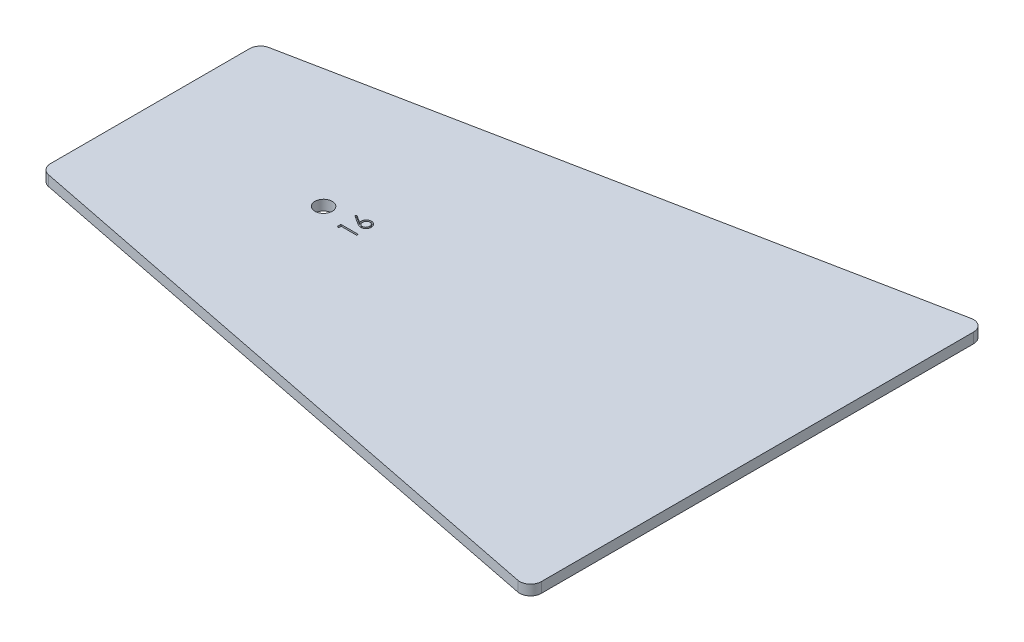
SolidWorks part; units mm, degrees
material "Acrylic (Medium-high impact)"
ref_plane "Front Plane" through (0, 0, 0) normal (0, 0, 1) x (1, 0, 0)
ref_plane "Top Plane" through (0, 0, 0) normal (0, 1, 0) x (1, 0, 0)
ref_plane "Right Plane" through (0, 0, 0) normal (1, 0, 0) x (0, 0, -1)
sketch "Sketch1" plane through (0, 0, 0) normal (0, 1, 0) x (1, 0, 0)
  line L0 (0, 0) -> (0, -355.6) construction
  line L1 (-63.5, 0) -> (63.5, 0)
  line L2 (63.5, 0) -> (134.2332, -355.6)
  line L3 (134.2332, -355.6) -> (-134.2332, -355.6)
  line L4 (-63.5, 0) -> (-134.2332, -355.6)
  dimension "D1" = 355.6
  dimension "D2" = 22.5
  dimension "D3" = 127
extrude "Boss-Extrude1" add sketch "Sketch1" along normal blind 5.9944
sketch "Sketch2" plane through (0, 5.9944, 0) normal (0, 1, 0) x (1, 0, 0)
  line L0 (0, 0) -> (0, -101.6) construction
  line L1 (63.5, 0) -> (-63.5, 0) construction
  circle A0 centre (0, -101.6) radius 5.08
  dimension "D1" = 10.16
  dimension "D2" = 101.6
extrude "Cut-Extrude1" cut sketch "Sketch2" against normal through all
sketch "Sketch3" plane through (0, 5.9944, 0) normal (0, 1, 0) x (1, 0, 0)
  line L0 (0, -119.38) -> (0, -101.6) construction
  line L2 (8.5085, -112.7791) -> (-8.5085, -112.7791) construction
  line L3 (8.5085, -112.7791) -> (8.5085, -125.9809) construction
  line L4 (8.5085, -125.9809) -> (-8.5085, -125.9809) construction
  line L5 (-8.5085, -112.7791) -> (-8.5085, -125.9809) construction
  line L6 (8.5085, -112.7791) -> (-8.5085, -125.9809) construction
  line L7 (8.5085, -125.9809) -> (-8.5085, -112.7791) construction
  text T0 "16" font "Century Gothic" height 10.16
  point P1 (0, -119.38)
  dimension "D2" = 17.78
extrude "Cut-Extrude2" cut sketch "Sketch3" against normal blind 1.27
fillet "Fillet1" radius 6.35 4 edges at (134.2332, 2.9972, 355.6) (-134.2332, 2.9972, 355.6) (-63.5, 2.9972, 0) (63.5, 2.9972, 0)
move or copy body "Body-Move/Copy1" bodies to move or copy 103 copy no rotation origin (0, 0, 177.8) rotation axis (0, 1, 0) rotation angle 90
